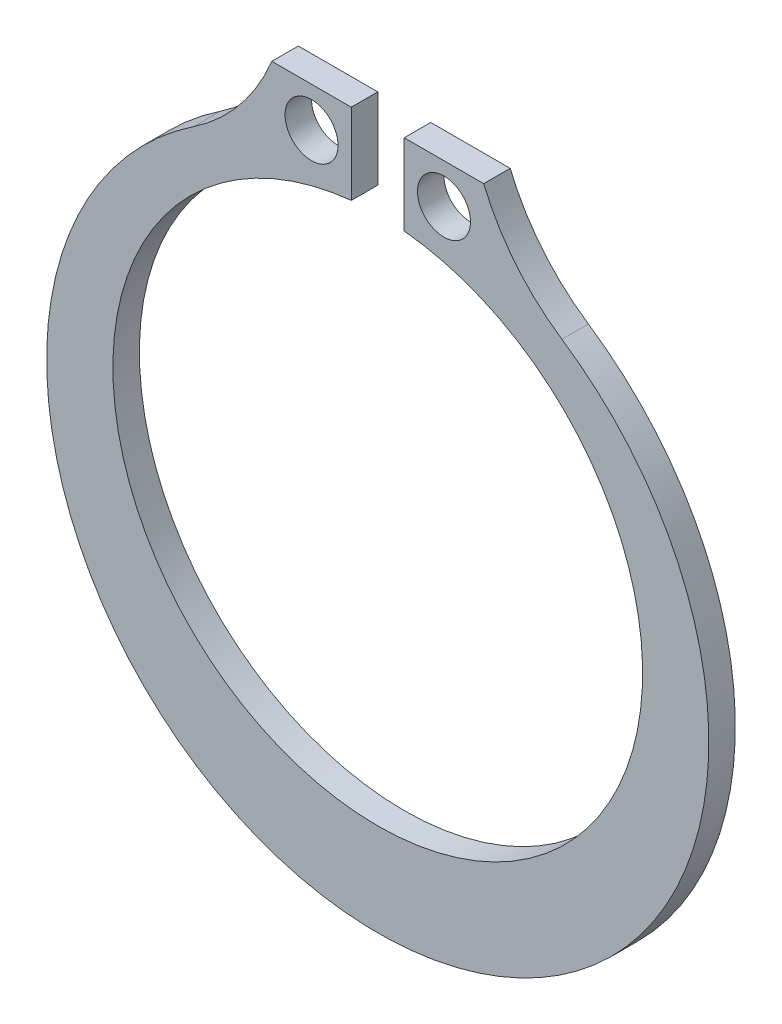
SolidWorks part; units mm, degrees
material "Alloy Steel"
ref_plane "Front Plane" through (0, 0, 0) normal (0, 0, 1) x (1, 0, 0)
ref_plane "Top Plane" through (0, 0, 0) normal (0, 1, 0) x (1, 0, 0)
ref_plane "Right Plane" through (0, 0, 0) normal (1, 0, 0) x (0, 0, -1)
sketch "Sketch1" plane through (0, 0, 0) normal (0, 0, 1) x (1, 0, 0)
  line L0 (0, 0) -> (0, 9.7102) construction
  line L1 (-4, 14) -> (-1, 14)
  line L2 (-1, 14) -> (-1, 10.9499)
  line L3 (1, 14) -> (1, 10.9499)
  line L4 (4, 14) -> (1, 14)
  arc A0 (-6.9519, 10.3885) -> (6.9519, 10.3885) centre (0, 0) ccw
  arc A2 (-1, 10.9499) -> (1, 10.9499) centre (0, 1) ccw
  arc A3 (-4, 14) -> (-6.9519, 10.3885) centre (-11.401, 17.0372) cw
  arc A4 (4, 14) -> (6.9519, 10.3885) centre (11.401, 17.0372) ccw
  circle A5 centre (-2.5, 12.5) radius 1
  circle A6 centre (2.5, 12.5) radius 1
  point P16 (0, 0)
  point P19 (-3.1935, 13.3479)
  dimension "D1" = 25
  dimension "D2" = 1
  dimension "D3" = 20
  dimension "D4" = 8
  dimension "D8" = 2
  dimension "D5" = 13
  dimension "D6" = 8
  dimension "D7" = 2
  dimension "D9" = 1.5
  dimension "D10" = 1.5
extrude "Boss-Extrude1" add sketch "Sketch1" along normal blind 1
